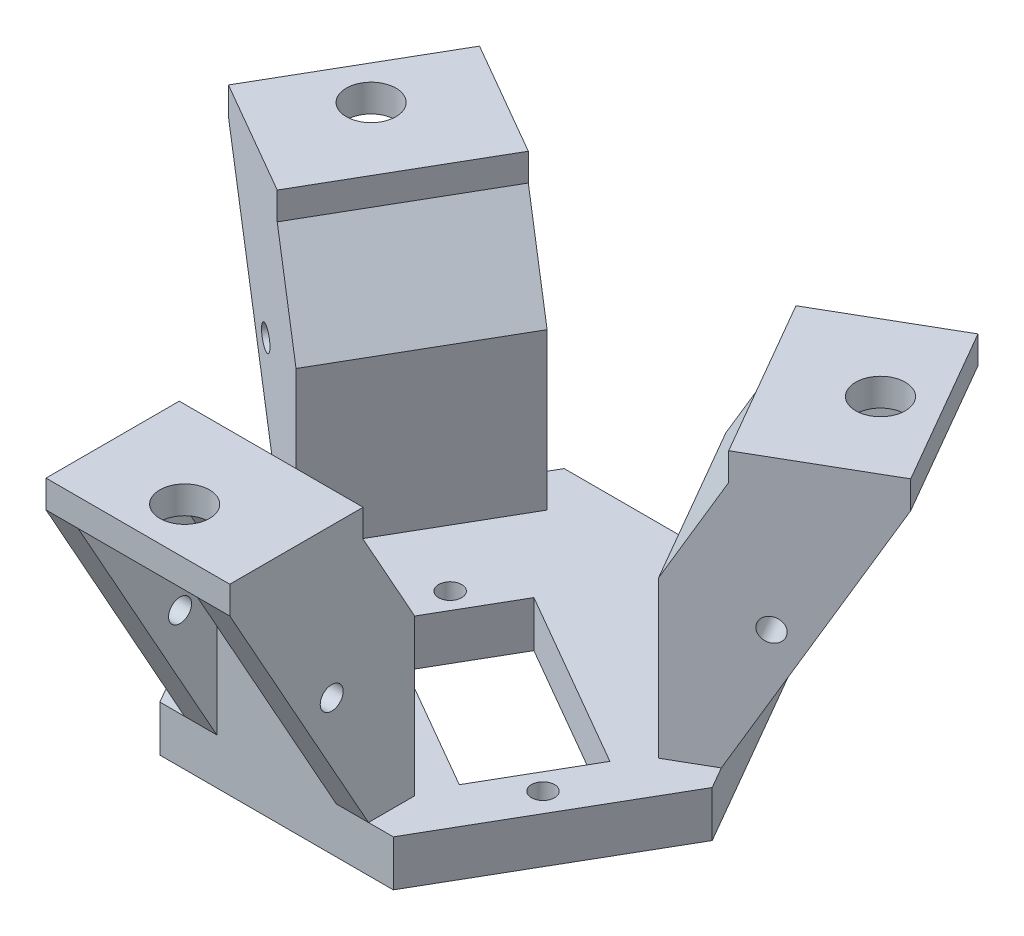
SolidWorks part; units mm, degrees
ref_plane "Front Plane" through (0, 0, 0) normal (0, 0, 1) x (1, 0, 0)
ref_plane "Top Plane" through (0, 0, 0) normal (0, 1, 0) x (1, 0, 0)
ref_plane "Right Plane" through (0, 0, 0) normal (1, 0, 0) x (0, 0, -1)
sketch "Sketch1" plane through (0, 0, 0) normal (0, 1, 0) x (1, 0, 0)
  line L0 (25.4034, 0) -> (12.7017, 22)
  line L1 (12.7017, 22) -> (-12.7017, 22)
  line L2 (-12.7017, 22) -> (-25.4034, 0)
  line L3 (-25.4034, 0) -> (-12.7017, -22)
  line L4 (-12.7017, -22) -> (12.7017, -22)
  line L5 (12.7017, -22) -> (25.4034, 0)
  circle A0 centre (0, 0) radius 25.4034 construction
  dimension "D1" = 22
extrude "Boss-Extrude1" add sketch "Sketch1" along normal blind 5
sketch "Sketch4" plane through (0, 5, 0) normal (0, 1, 0) x (1, 0, 0)
  line L0 (-12.7017, -22) -> (12.7017, -22) construction
  line L1 (-10, -22) -> (10, -22)
  line L2 (-10, -22) -> (-10, -17)
  line L3 (-10, -17) -> (10, -17)
  line L4 (10, -22) -> (10, -17)
  point P6 (0, -22)
  point P7 (0, -22)
  dimension "D1" = 20
  dimension "D2" = 5
extrude "Boss-Extrude3" add sketch "Sketch4" along normal blind 17
sketch "Sketch2" plane through (0, 0, 0) normal (1, 0, 0) x (0, 0, -1)
  line L1 (-22, 5) -> (-22, 0) construction
  line L3 (-22, 22) -> (-22, 5)
  line L5 (-22, 5) -> (-31.5, 22)
  line L7 (-31.5, 22) -> (-22, 22)
  line L8 (-22, 22) -> (-17, 22) construction
  circle A1 centre (-26, 18.75) radius 1.25
  point P1 (-31.5548, 21.8272)
  point P4 (-31.5, 21.2661)
  point P5 (-32.9048, 22)
  point P7 (-22.1622, 22)
  dimension "D1" = 2.5
  dimension "D2" = 4
  dimension "D3" = 9.5
  dimension "D4" = 3.25
extrude "Boss-Extrude2" add sketch "Sketch2" along normal up to surface (3.5 mm away) from offset 6.5 up to face at (10, 13.5, 19.5)
mirror "Mirror1" about plane through (0, 0, 0) normal (1, 0, 0) of "Boss-Extrude3", "Boss-Extrude2"
sketch "Sketch5" plane through (0, 0, 0) normal (0, 0, 1) x (1, 0, 0)
  line L0 (0, 0) -> (0, 15.7855) construction
pattern_circular "CirPattern1" count 3 over 360 about axis through (0, 0, 0) along (0, 1, 0) of "Mirror1", "Boss-Extrude3", "Boss-Extrude2"
sketch "Sketch3" plane through (0, 5, 0) normal (0, 1, 0) x (1, 0, 0)
  line L0 (-5.1962, 3) -> (0, 0) construction
  line L1 (-2.1962, 8.1962) -> (17.376, -3.1038)
  line L2 (-2.1962, 8.1962) -> (-8.1962, -2.1962)
  line L3 (-8.1962, -2.1962) -> (11.376, -13.4962)
  line L4 (17.376, -3.1038) -> (11.376, -13.4962)
  line L5 (12.7017, -22) -> (25.4034, 0) construction
  point P7 (-5.1962, 3)
  dimension "D1" = 22.6
  dimension "D2" = 12
  dimension "D3" = 6
extrude "Cut-Extrude1" cut sketch "Sketch3" against normal up to next
sketch "Sketch6" plane through (0, 5, 0) normal (0, 1, 0) x (1, 0, 0)
  line L0 (-2.1962, 8.1962) -> (-8.1962, -2.1962) construction
  line L1 (11.376, -13.4962) -> (17.376, -3.1038) construction
  line L2 (-7.3612, 4.25) -> (16.5411, -9.55) construction
  circle A0 centre (-7.3612, 4.25) radius 1.25
  circle A1 centre (16.5411, -9.55) radius 1.25
  point P8 (14.376, -8.3)
  point P9 (-5.1962, 3)
  point P10 (-7.3612, 4.25)
  dimension "D3" = 2.5
  dimension "D1" = 2.5
  dimension "D2" = 2.5
extrude "Cut-Extrude2" cut sketch "Sketch6" against normal up to next
sketch "Sketch10" plane through (0, 22, 0) normal (0, 1, 0) x (1, 0, 0)
  line L0 (-22.2798, 24.4103) -> (-9.7224, 17.1603)
  line L1 (-9.7224, 17.1603) -> (-19.7224, -0.1603)
  line L2 (-19.7224, -0.1603) -> (-32.2798, 7.0897)
  line L3 (-32.2798, 7.0897) -> (-30.5298, 10.1208)
  line L4 (-30.5298, 10.1208) -> (-22.3026, 5.3708)
  line L5 (-22.3026, 5.3708) -> (-15.8026, 16.6292)
  line L6 (-15.8026, 16.6292) -> (-24.0298, 21.3792)
  line L7 (-24.0298, 21.3792) -> (-22.2798, 24.4103)
sketch "Sketch11" plane through (-5, 0, 8.6603) normal (-0.5, 0, 0.866) x (0.866, 0, 0.5)
  line L0 (-31.5, 22) -> (-37.0882, 32)
  line L1 (-22, 5) -> (-31.5, 22) construction
  point P5 (-31.5, 22)
  point P8 (-37.7257, 33.1407)
  dimension "D1" = 10
sweep "Sweep1" add profiles "Sketch10" path "Sketch11"
sketch "Sketch12" plane through (0, 32, 0) normal (0, 1, 0) x (1, 0, 0)
  line L0 (-27.1194, 27.2044) -> (-14.562, 19.9544)
  line L1 (-27.1194, 27.2044) -> (-37.1194, 9.8839)
  line L2 (-14.562, 19.9544) -> (-24.562, 2.6339)
  line L3 (-37.1194, 9.8839) -> (-24.562, 2.6339)
  line L4 (-37.1194, 9.8839) -> (-24.562, 2.6339) construction
extrude "Boss-Extrude4" add sketch "Sketch12" along normal blind 3
sketch "Sketch13" plane through (0, 35, 0) normal (0, 1, 0) x (1, 0, 0)
  line L0 (-27.7128, 16) -> (0, 0) construction
  line L1 (-24.562, 2.6339) -> (-14.562, 19.9544) construction
  circle A0 centre (-27.7128, 16) radius 2.7
  point P7 (-19.562, 11.2941)
  point P8 (0, 0)
  dimension "D1" = 5.4
  dimension "D2" = 32
extrude "Cut-Extrude3" cut sketch "Sketch13" against normal up to next
pattern_circular "CirPattern2" count 3 over 360 about axis through (0, 0, 0) along (0, 1, 0) of "Sweep1", "Boss-Extrude4", "Cut-Extrude3"
